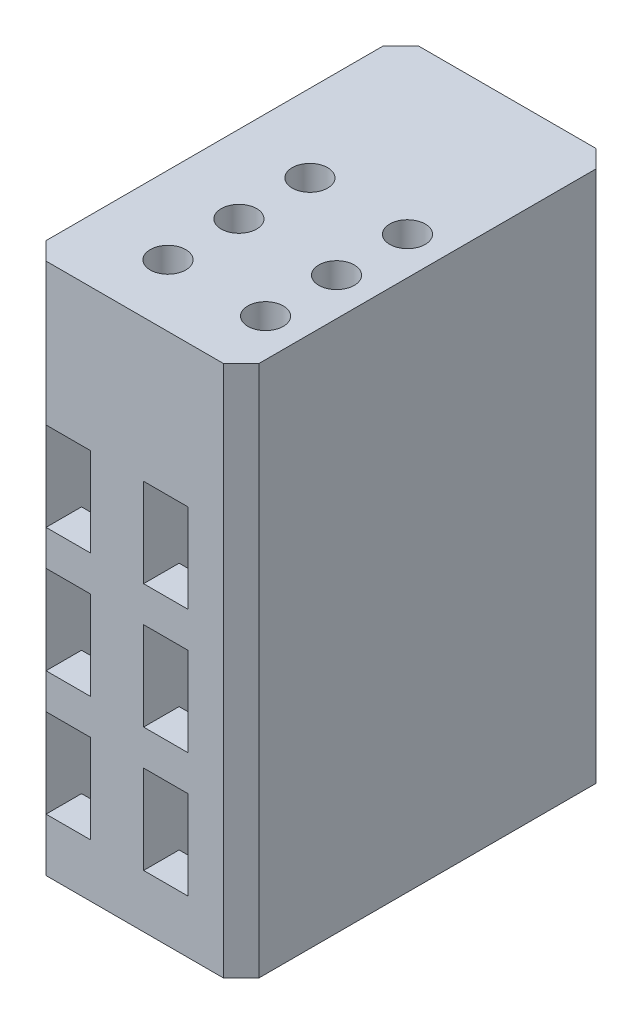
SolidWorks part; units mm, degrees
ref_plane "Спереди" through (0, 0, 0) normal (0, 0, 1) x (1, 0, 0)
ref_plane "Сверху" through (0, 0, 0) normal (0, 1, 0) x (1, 0, 0)
ref_plane "Справа" through (0, 0, 0) normal (1, 0, 0) x (0, 0, -1)
sketch "Эскиз1" plane through (0, 0, 0) normal (0, 1, 0) x (1, 0, 0)
  line L0 (0, 0) -> (0, 20) construction
  line L1 (5, 0) -> (-5, 0)
  line L2 (-5, 0) -> (-6, 1)
  line L3 (-6, 1) -> (-6, 10.5)
  line L4 (-5, 0) -> (-6, 0) construction
  line L5 (-6, 0) -> (-6, 1) construction
  line L6 (-6, 10.5) -> (-5, 10.5) construction
  line L7 (-5, 10.5) -> (-5, 2)
  line L8 (-5, 2) -> (-0.5, 2)
  line L9 (0, 2.0136) -> (0, 0) construction
  line L10 (-0.5, 2) -> (-0.5, 10.5)
  line L11 (-0.5, 2) -> (0, 2) construction
  line L12 (0.5, 2) -> (0.5, 10.5)
  line L13 (5, 10.5) -> (5, 2)
  line L14 (5, 2) -> (0.5, 2)
  line L15 (5, 0) -> (6, 1)
  line L16 (6, 1) -> (6, 10.5)
  line L17 (-6, 10.5) -> (-5, 10.5)
  line L18 (-0.5, 10.5) -> (0.5, 10.5)
  line L19 (5, 10.5) -> (6, 10.5)
  line L20 (-2.75, 2) -> (-2.75, 0) construction
  dimension "D1" = 20
  dimension "D2" = 1
  dimension "D3" = 1
  dimension "D4" = 5
  dimension "D5" = 9.5
  dimension "D6" = 1
  dimension "D7" = 2
  dimension "D8" = 0.5
  dimension "D9" = 8.5
extrude "Бобышка-Вытянуть1" add sketch "Эскиз1" along normal blind 30
mirror "Зеркальное отражение1" about plane through (-0.5, 30, -10.5) normal (0, 0, 1) of "Бобышка-Вытянуть1"
sketch "Эскиз2" plane through (0, 30, 0) normal (0, 1, 0) x (1, 0, 0)
  line L0 (-2.75, 2) -> (-0.5, 2) construction
  line L1 (-0.5, 2) -> (-5, 2) construction
  line L2 (-1.625, 2) -> (-1.625, 3.5) construction
  line L4 (-1.625, 3.5) -> (-1.625, 7.5) construction
  line L5 (-1.625, 7.5) -> (-1.625, 11.5) construction
  line L6 (-1.625, 11.5) -> (-1.625, 19) construction
  line L7 (-0.5, 19) -> (-5, 19) construction
  line L8 (-5, 2) -> (-0.5, 2)
  line L9 (-5, 2) -> (-5, 19)
  line L10 (-5, 19) -> (-0.5, 19)
  line L11 (-0.5, 2) -> (-0.5, 19)
  circle A1 centre (-1.625, 11.5) radius 1
  circle A2 centre (-1.625, 7.5) radius 1
  circle A3 centre (-1.625, 3.5) radius 1
  dimension "D4" = 2
  dimension "D1" = 7.5
  dimension "D2" = 4
  dimension "D3" = 4
  dimension "D5" = 3
extrude "Бобышка-Вытянуть2" add sketch "Эскиз2" against normal blind 3
sketch "Эскиз3" plane through (0, 27, 0) normal (0, -1, 0) x (1, 0, 0)
  line L0 (-0.5, -2) -> (-5, -2) construction
  line L1 (-0.5, -19) -> (-2.5, -19)
  line L2 (-0.5, -19) -> (-0.5, -2)
  line L3 (-0.5, -2) -> (-2.5, -2)
  line L4 (-2.5, -19) -> (-2.5, -13)
  line L5 (-1.625, -3.5) -> (-0.5, -3.5) construction
  line L6 (-1.625, -7.5) -> (-1.625, -6) construction
  line L8 (-0.5, -3.5) -> (-0.5, -5)
  line L9 (-0.5, -5) -> (-2.5, -5)
  line L11 (-1.625, -6) -> (-0.5, -6)
  line L12 (-1.625, -6) -> (-2.5, -6)
  line L13 (-1.625, -7.5) -> (-1.625, -9) construction
  line L14 (-1.625, -9) -> (-2.5, -9)
  line L15 (-1.625, -9) -> (-0.5, -9)
  line L16 (-2.5, -6) -> (-2.5, -5)
  line L17 (-1.625, -11.5) -> (-1.625, -10) construction
  line L18 (-1.625, -10) -> (-0.5, -10)
  line L19 (-1.625, -10) -> (-2.5, -10)
  line L20 (-1.625, -11.5) -> (-1.625, -13) construction
  line L21 (-1.625, -13) -> (-0.5, -13)
  line L22 (-1.625, -13) -> (-2.5, -13)
  line L23 (-2.5, -10) -> (-2.5, -9)
  line M16 (-0.5, -19) -> (-0.5, -2)
  line M19 (-5, -19) -> (-0.5, -19)
  dimension "D1" = 2
  dimension "D2" = 1.5
  dimension "D3" = 1.5
  dimension "D4" = 1.5
  dimension "D5" = 1.5
extrude "Бобышка-Вытянуть3" add sketch "Эскиз3" along normal blind 27 contours L21 L22 L4 M19 M16 | L23 L19 L18 L2 L15 L14 | L16 L12 L11 L2 L9
pattern_linear "Линейный массив1" count 2 spacing 5.5 along (1, 0, 0) of "Бобышка-Вытянуть2"
pattern_linear "Линейный массив2" count 2 spacing 5.5 along (1, 0, 0) of "Бобышка-Вытянуть3"
sketch "Эскиз5" plane through (0, 0, -21) normal (0, 0, -1) x (-1, 0, 0)
  line L0 (5, 30) -> (5, 20) construction
  line L1 (5, 30) -> (5, 0) construction
  line L3 (5, 20) -> (2.5, 20)
  line L4 (5, 20) -> (5, 17)
  line L5 (5, 17) -> (2.5, 17)
  line L6 (2.5, 20) -> (2.5, 17)
  dimension "D1" = 10
  dimension "D2" = 2.5
  dimension "D3" = 3
extrude "Вырез-Вытянуть1" cut sketch "Эскиз5" against normal up to next contours L3 L6 L5 L4
pattern_linear "Линейный массив3" count 3 spacing 7 along (0, -1, 0) of "Вырез-Вытянуть1"
pattern_linear "Линейный массив4" count 2 spacing 5.5 along (1, 0, 0) of "Линейный массив3", "Вырез-Вытянуть1"
sketch "Эскиз6" plane through (0, 0, 0) normal (0, 0, 1) x (1, 0, 0)
  line L0 (-5, 30) -> (-5, 22) construction
  line L1 (-5, 30) -> (-5, 0) construction
  line L3 (-5, 22) -> (-2.5, 22)
  line L4 (-5, 22) -> (-5, 17)
  line L5 (-5, 17) -> (-2.5, 17)
  line L6 (-2.5, 22) -> (-2.5, 17)
  dimension "D1" = 8
  dimension "D2" = 5
  dimension "D3" = 2.5
extrude "Вырез-Вытянуть2" cut sketch "Эскиз6" against normal up to next
pattern_linear "Линейный массив5" count 3 spacing 7 along (0, -1, 0) of "Вырез-Вытянуть2"
pattern_linear "Линейный массив7" count 2 spacing 5.5 along (1, 0, 0) of "Линейный массив5", "Вырез-Вытянуть2"
